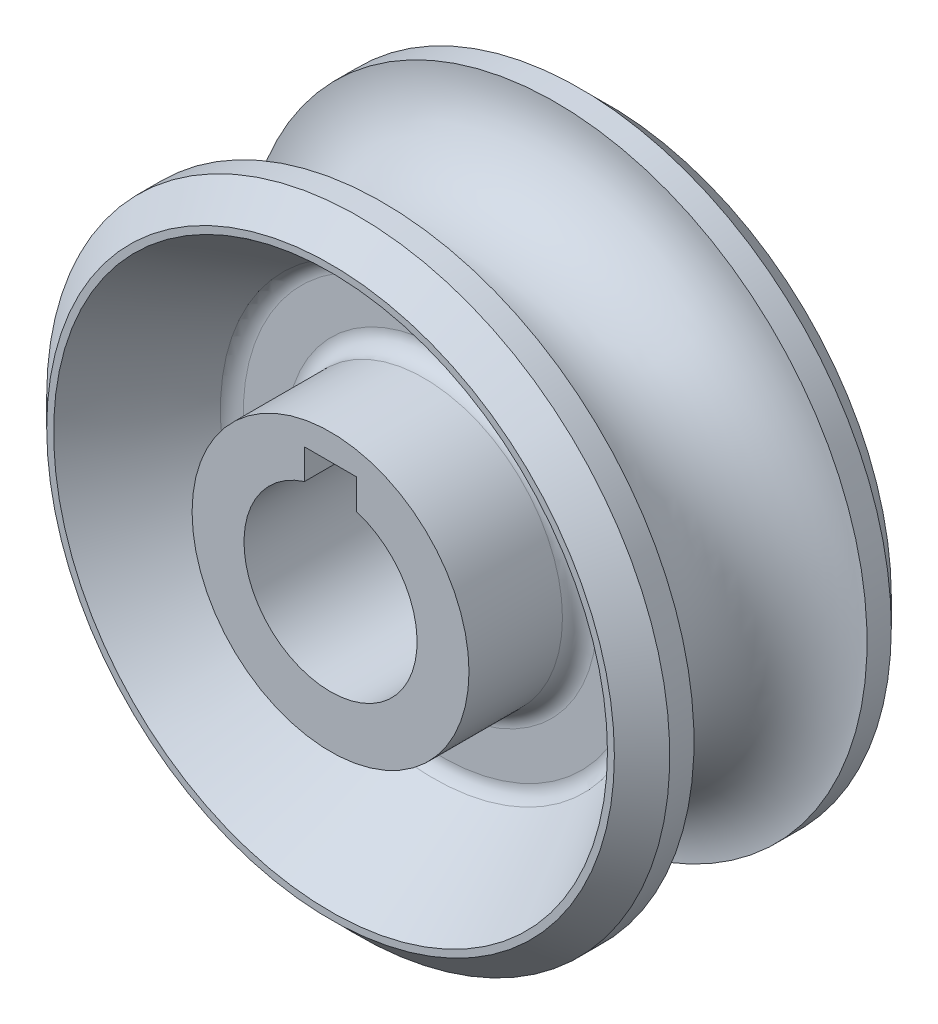
SolidWorks part; units mm, degrees
material "AISI 1020"
ref_plane "Front Plane" through (0, 0, 0) normal (0, 0, 1) x (1, 0, 0)
ref_plane "Top Plane" through (0, 0, 0) normal (0, 1, 0) x (1, 0, 0)
ref_plane "Right Plane" through (0, 0, 0) normal (1, 0, 0) x (0, 0, -1)
sketch "Sketch1" plane through (0, 0, 0) normal (0, 0, 1) x (1, 0, 0)
  circle A0 centre (0, 0) radius 7.9375
  circle A1 centre (0, 0) radius 28.575
  dimension "D1" = 57.15
  dimension "D2" = 15.875
extrude "Base" add sketch "Sketch1" along normal mid plane 25.4
sketch "Sketch3" plane through (0, 0, 0) normal (1, 0, 0) x (0, 0, -1)
  line L0 (12.7, 28.575) -> (-12.7, 28.575) construction
  line L1 (0, 0) -> (16.2737, 0) construction
  circle A0 centre (0, 28.575) radius 7.9375
  dimension "D1" = 15.875
revolve "Cut-Revolve1" cut sketch "Sketch3" angle 360 about L1
sketch "Sketch4" plane through (0, 0, 0) normal (1, 0, 0) x (0, 0, -1)
  line L0 (12.7, 25.4) -> (12.7, 12.7)
  line L1 (12.7, -28.575) -> (12.7, 28.575) construction
  line L2 (12.7, 12.7) -> (2.54, 12.7)
  line L3 (2.54, 12.7) -> (2.54, 19.05)
  line L4 (2.54, 19.05) -> (12.7, 25.4)
  line L5 (0, 0) -> (14.4032, 0) construction
  line L6 (0, 0) -> (0, 31.5621) construction
  line L7 (-2.54, 12.7) -> (-2.54, 19.05)
  line L8 (-12.7, 12.7) -> (-2.54, 12.7)
  line L9 (-12.7, 25.4) -> (-12.7, 12.7)
  line L10 (-2.54, 19.05) -> (-12.7, 25.4)
  dimension "D1" = 10.16
  dimension "D2" = 6.35
  dimension "D3" = 50.8
  dimension "D4" = 25.4
revolve "Cut-Revolve2" cut sketch "Sketch4" angle 360 about L5
chamfer "Chamfer1" distance 2.54 angle 45 2 edges at (28.575, 0, -12.7) (28.575, 0, 12.7)
fillet "Fillet1" radius 1.5875 4 edges at (19.05, 0, -2.54) (12.7, 0, -2.54) (12.7, 0, 2.54) (19.05, 0, 2.54)
sketch "Sketch5" plane through (0, 0, 0) normal (0, 0, 1) x (1, 0, 0)
  line L1 (-2.3876, 10.3251) -> (2.3876, 10.3251)
  line L2 (-2.3876, 10.3251) -> (-2.3876, 0)
  line L3 (-2.3876, 0) -> (2.3876, 0)
  line L4 (2.3876, 10.3251) -> (2.3876, 0)
  circle A3 centre (0, 0) radius 7.9375 construction
  dimension "D1" = 4.7752
  dimension "D2" = 2.3876
extrude "Cut-Extrude1" cut sketch "Sketch5" against normal through all both and the other way through all
